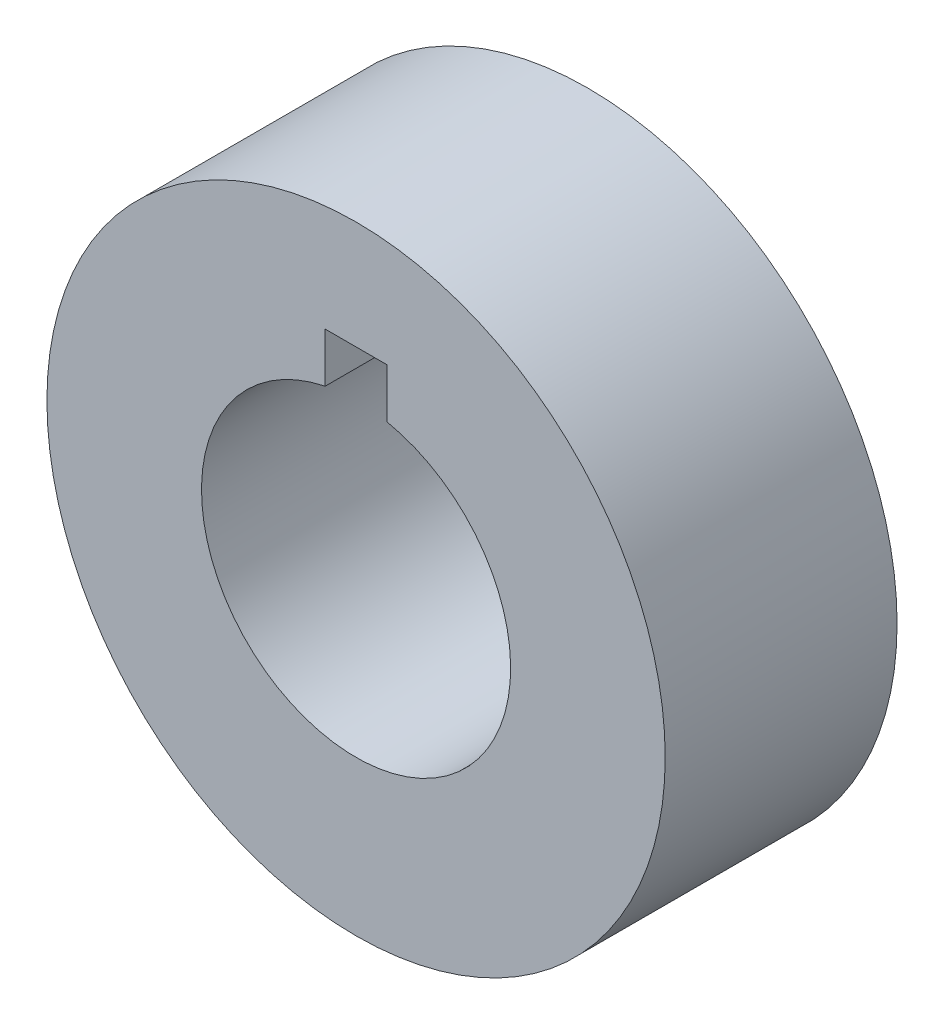
SolidWorks part; units mm, degrees
ref_plane "Front Plane" through (0, 0, 0) normal (0, 0, 1) x (1, 0, 0)
ref_plane "Top Plane" through (0, 0, 0) normal (0, 1, 0) x (1, 0, 0)
ref_plane "Right Plane" through (0, 0, 0) normal (1, 0, 0) x (0, 0, -1)
sketch "Sketch3" plane through (0, 0, 0) normal (0, 0, 1) x (1, 0, 0)
  line L0 (0, 0) -> (0, 16.51) construction
  line L1 (-2.54, 16.51) -> (2.54, 16.51)
  line L2 (2.54, 16.51) -> (2.54, 12.4434)
  line L3 (-2.54, 16.51) -> (-2.54, 12.4434)
  circle A0 centre (0, 0) radius 25.4
  arc A1 (-2.54, 12.4434) -> (2.54, 12.4434) centre (0, 0) ccw
  dimension "D1" = 25.4
  dimension "D2" = 50.8
  dimension "D3" = 16.51
  dimension "D4" = 2.54
extrude "Boss-Extrude1" add sketch "Sketch3" along normal blind 19.05 contours A1 L2 L1 L3
